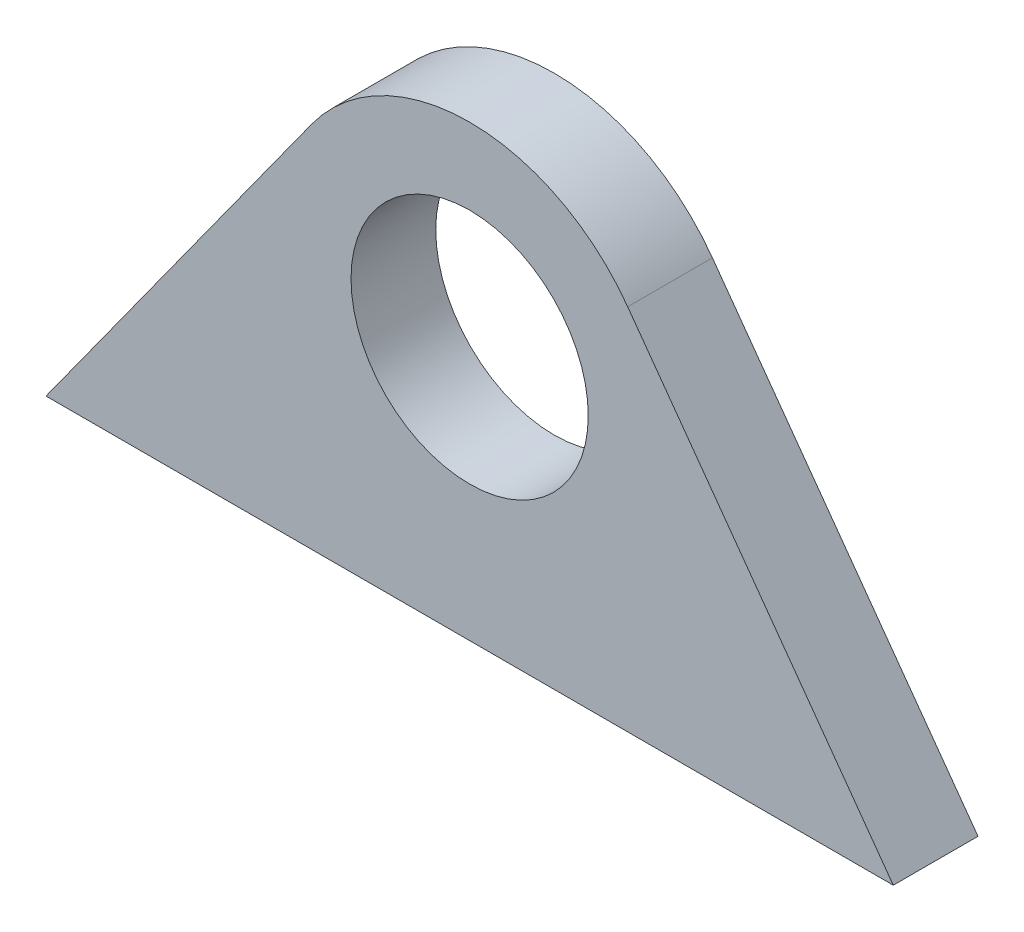
SolidWorks part; units mm, degrees
ref_plane "Front Plane" through (0, 0, 0) normal (0, 0, 1) x (1, 0, 0)
ref_plane "Top Plane" through (0, 0, 0) normal (0, 1, 0) x (1, 0, 0)
ref_plane "Right Plane" through (0, 0, 0) normal (1, 0, 0) x (0, 0, -1)
sketch "Sketch1" plane through (0, 0, 0) normal (0, 0, 1) x (1, 0, 0)
  line L0 (-25, -15) -> (25, -15)
  line L1 (-25, -15) -> (-9.3267, 6.7278)
  line L2 (25, -15) -> (9.3267, 6.7278)
  circle A0 centre (0, 0) radius 7
  arc A1 (9.3267, 6.7278) -> (-9.3267, 6.7278) centre (0, 0) ccw
  point P4 (9.0321, 7.1184)
  point P7 (0, -15)
  point P10 (-9.8833, 5.8796)
  dimension "D1" = 14
  dimension "D2" = 23
  dimension "D3" = 50
  dimension "D4" = 15
  dimension "D5" = 0
extrude "Boss-Extrude1" add sketch "Sketch1" along normal blind 5
